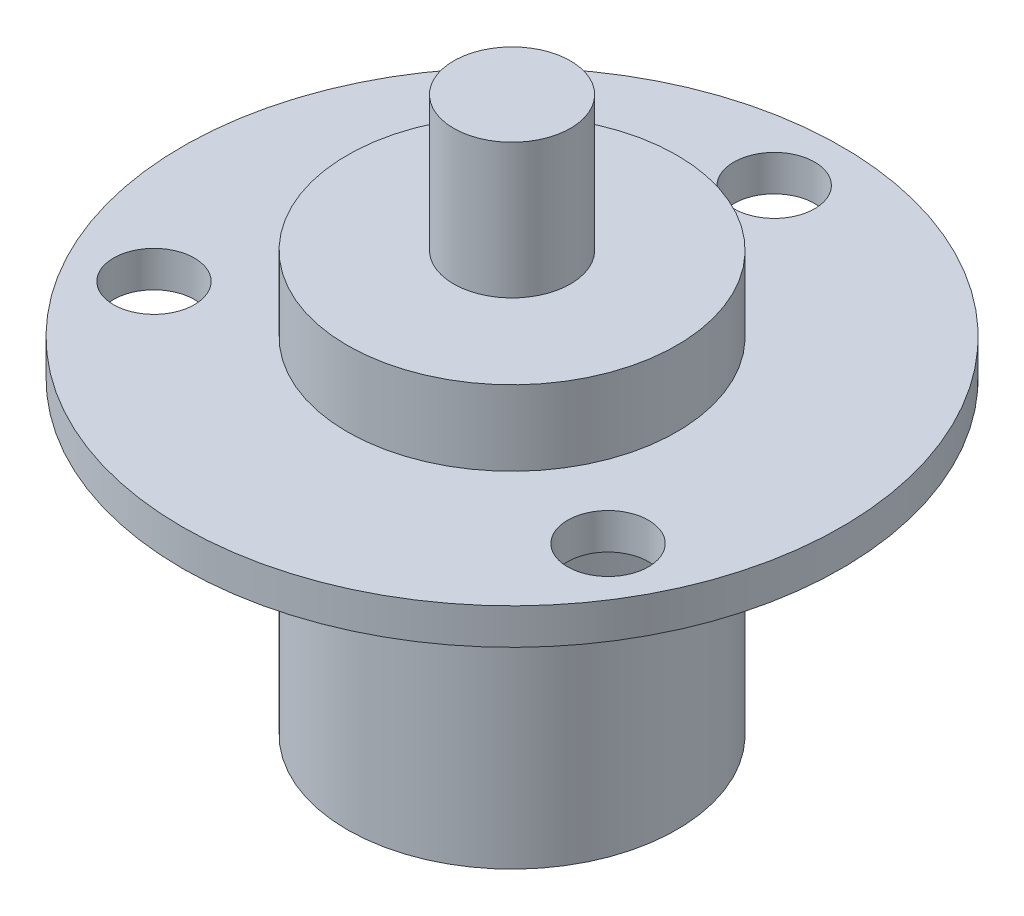
SolidWorks part; units mm, degrees
ref_plane "Front Plane" through (0, 0, 0) normal (0, 0, 1) x (1, 0, 0)
ref_plane "Top Plane" through (0, 0, 0) normal (0, 1, 0) x (1, 0, 0)
ref_plane "Right Plane" through (0, 0, 0) normal (1, 0, 0) x (0, 0, -1)
sketch "Sketch1" plane through (0, 0, 0) normal (0, 1, 0) x (1, 0, 0)
  circle A0 centre (0, 0) radius 22
  dimension "D1" = 44
extrude "Boss-Extrude1" add sketch "Sketch1" along normal blind 2.4
sketch "Sketch2" plane through (0, 2.4, 0) normal (0, 1, 0) x (1, 0, 0)
  circle A0 centre (0, 0) radius 11
  dimension "D1" = 22
extrude "Boss-Extrude2" add sketch "Sketch2" along normal blind 5
sketch "Sketch3" plane through (0, 7.4, 0) normal (0, 1, 0) x (1, 0, 0)
  circle A0 centre (0, 0) radius 3.9
  dimension "D1" = 7.8
extrude "Boss-Extrude3" add sketch "Sketch3" along normal blind 9
sketch "Sketch4" plane through (0, 0, 0) normal (0, -1, 0) x (1, 0, 0)
  circle A0 centre (0, 0) radius 11
  dimension "D1" = 22
extrude "Boss-Extrude4" add sketch "Sketch4" along normal blind 20.6
sketch "Sketch5" plane through (0, 2.4, 0) normal (0, 1, 0) x (1, 0, 0)
  line L0 (0, 0) -> (0, 17.5) construction
  line L1 (0, 0) -> (-15.1554, -8.75) construction
  line L2 (0, 0) -> (15.1554, -8.75) construction
  circle A0 centre (0, 0) radius 17.5 construction
  circle A1 centre (0, 17.5) radius 2.7
  circle A2 centre (-15.1554, -8.75) radius 2.7
  circle A3 centre (15.1554, -8.75) radius 2.7
  dimension "D1" = 35
  dimension "D4" = 5.4
  dimension "D2" = 120
  dimension "D3" = 120
extrude "Cut-Extrude1" cut sketch "Sketch5" against normal through all
equation "\"5mmm\"=1.45669"
